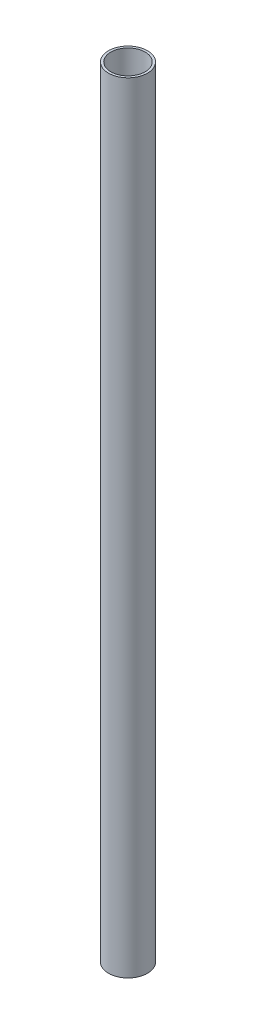
SolidWorks part; units mm, degrees
ref_plane "Front Plane" through (0, 0, 0) normal (0, 0, 1) x (1, 0, 0)
ref_plane "Top Plane" through (0, 0, 0) normal (0, 1, 0) x (1, 0, 0)
ref_plane "Right Plane" through (0, 0, 0) normal (1, 0, 0) x (0, 0, -1)
sketch "Sketch1" plane through (0, 0, 0) normal (0, 1, 0) x (1, 0, 0)
  circle A0 centre (0, 0) radius 25
  dimension "D1" = 50
extrude "Boss-Extrude1" add sketch "Sketch1" along normal blind 1000
sketch "Sketch2" plane through (0, 0, 0) normal (0, -1, 0) x (1, 0, 0)
  circle A2 centre (0, 0) radius 22
  circle A3 centre (0, 0) radius 22
  dimension "D1" = 3
extrude "Cut-Extrude1" cut sketch "Sketch2" against normal through all
ref_plane "Plane1" through (0, 0, 25) normal (0, 0, 1) x (1, 0, 0)
